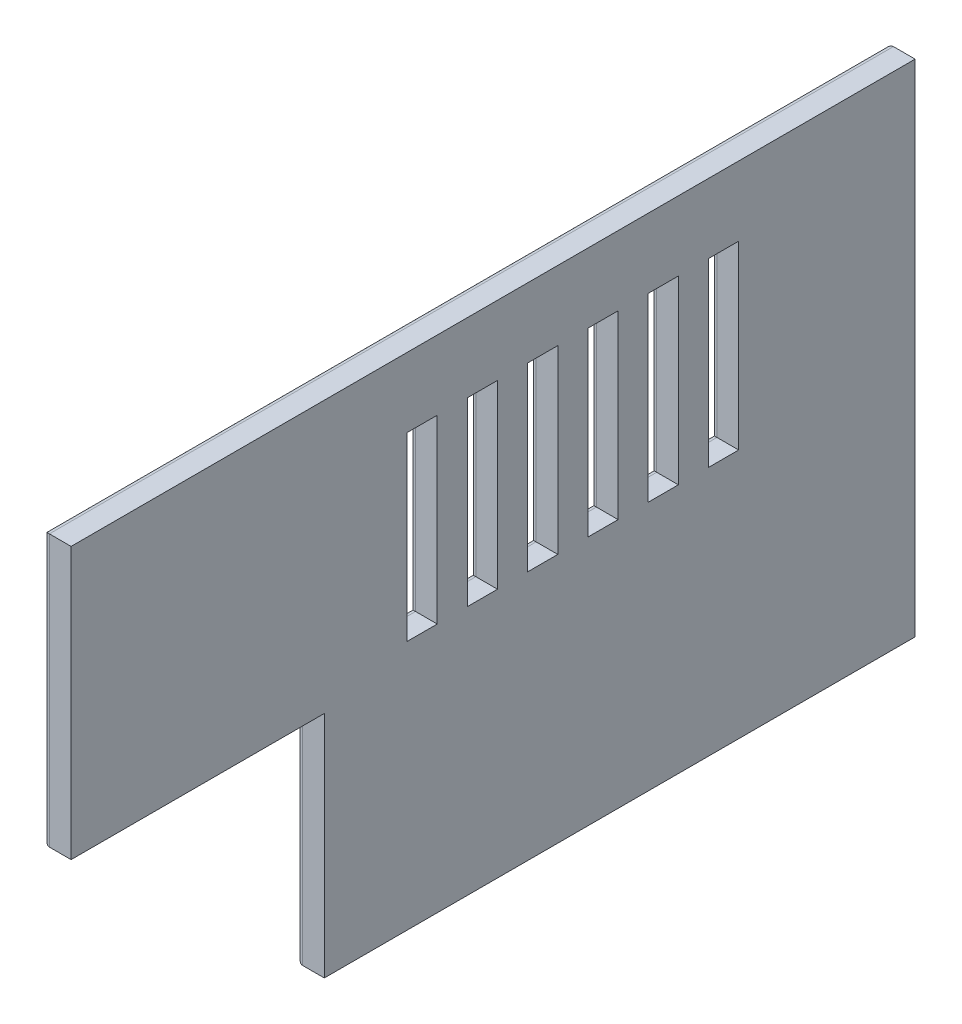
SolidWorks part; units mm, degrees
ref_plane "Front Plane" through (0, 0, 0) normal (0, 0, 1) x (1, 0, 0)
ref_plane "Top Plane" through (0, 0, 0) normal (0, 1, 0) x (1, 0, 0)
ref_plane "Right Plane" through (0, 0, 0) normal (1, 0, 0) x (0, 0, -1)
sketch "Sketch1" plane through (0, 0, 0) normal (1, 0, 0) x (0, 0, -1)
  line L1 (-27, 80.7143) -> (113, 80.7143)
  line L2 (-27, 80.7143) -> (-27, -19.2857)
  line L3 (-27, -19.2857) -> (13, -19.2857)
  line L4 (113, 80.7143) -> (113, -2.2857)
  line L5 (-27, 80.7143) -> (0.7646, -2.2857) construction
  line L6 (-27, -19.2857) -> (113, 80.7143) construction
  line L9 (113, -2.2857) -> (13, -2.2857)
  line L10 (13, -19.2857) -> (13, -2.2857)
  point P0 (0, 0)
  dimension "D1" = 100
  dimension "D2" = 140
  dimension "D3" = 17
  dimension "D4" = 100
  dimension "D5" = 13
extrude "Boss-Extrude1" add sketch "Sketch1" along normal blind 4.6
sketch "Sketch2" plane through (4.6, 0, 0) normal (1, 0, 0) x (0, 0, -1)
  line L1 (-27, -19.2857) -> (15, -19.2857)
  line L2 (-27, -19.2857) -> (-27, 35.7143)
  line L3 (-27, 35.7143) -> (15, 35.7143)
  line L4 (15, -19.2857) -> (15, 35.7143)
  dimension "D1" = 55
  dimension "D2" = 42
extrude "Cut-Extrude1" cut sketch "Sketch2" against normal through all
sketch "Sketch4" plane through (0, 0, 0) normal (-1, 0, 0) x (0, 0, 1)
  line L0 (-38.7333, 39.1947) -> (-38.7333, 69.1947)
  line L1 (-28.7333, 39.1947) -> (-33.7333, 39.1947)
  line L2 (-28.7333, 39.1947) -> (-28.7333, 69.1947)
  line L3 (-28.7333, 69.1947) -> (-33.7333, 69.1947)
  line L4 (-33.7333, 39.1947) -> (-33.7333, 69.1947)
  line L5 (-38.7333, 39.1947) -> (-43.7333, 39.1947)
  line L6 (-43.7333, 39.1947) -> (-43.7333, 69.1947)
  line L7 (-38.7333, 69.1947) -> (-43.7333, 69.1947)
  line L8 (-48.7333, 39.1947) -> (-48.7333, 69.1947)
  line L9 (-48.7333, 39.1947) -> (-53.7333, 39.1947)
  line L10 (-53.7333, 39.1947) -> (-53.7333, 69.1947)
  line L11 (-48.7333, 69.1947) -> (-53.7333, 69.1947)
  line L12 (-58.7333, 39.1947) -> (-58.7333, 69.1947)
  line L13 (-58.7333, 39.1947) -> (-63.7333, 39.1947)
  line L14 (-63.7333, 39.1947) -> (-63.7333, 69.1947)
  line L15 (-58.7333, 69.1947) -> (-63.7333, 69.1947)
  line L16 (-68.7333, 39.1947) -> (-68.7333, 69.1947)
  line L17 (-68.7333, 39.1947) -> (-73.7333, 39.1947)
  line L18 (-73.7333, 39.1947) -> (-73.7333, 69.1947)
  line L19 (-68.7333, 69.1947) -> (-73.7333, 69.1947)
  line L20 (-78.7333, 39.1947) -> (-78.7333, 69.1947)
  line L21 (-78.7333, 39.1947) -> (-83.7333, 39.1947)
  line L22 (-83.7333, 39.1947) -> (-83.7333, 69.1947)
  line L23 (-78.7333, 69.1947) -> (-83.7333, 69.1947)
  line L24 (27, 80.7143) -> (27, 35.7143) construction
  line L25 (-15, 35.7143) -> (27, 35.7143) construction
  dimension "D1" = 5
  dimension "D2" = 30
  dimension "D4" = 55.7333
  dimension "D5" = 65.7333
  dimension "D6" = 3.4804
  dimension "D3" = 6
extrude "Cut-Extrude3" cut sketch "Sketch4" against normal blind 10
fillet "Fillet1" radius 1 30 edges at (0, -2.2857, -64) (0, 39.2143, -113) (0, 80.7143, -43) (0, 58.2143, 27) (0, 35.7143, 6) (0, 16.7143, -15) (0, 69.1947, -81.2333) (0, 54.1947, -83.7333) (0, 39.1947, -81.2333) (0, 54.1947, -78.7333) (0, 69.1947, -71.2333) (0, 54.1947, -73.7333) (0, 39.1947, -71.2333) (0, 54.1947, -68.7333) (0, 69.1947, -61.2333) (0, 54.1947, -63.7333) (0, 39.1947, -61.2333) (0, 54.1947, -58.7333) (0, 69.1947, -51.2333) (0, 54.1947, -53.7333) (0, 39.1947, -51.2333) (0, 54.1947, -48.7333) (0, 69.1947, -41.2333) (0, 54.1947, -43.7333) (0, 39.1947, -41.2333) (0, 54.1947, -38.7333) (0, 54.1947, -33.7333) (0, 39.1947, -31.2333) (0, 54.1947, -28.7333) (0, 69.1947, -31.2333)
